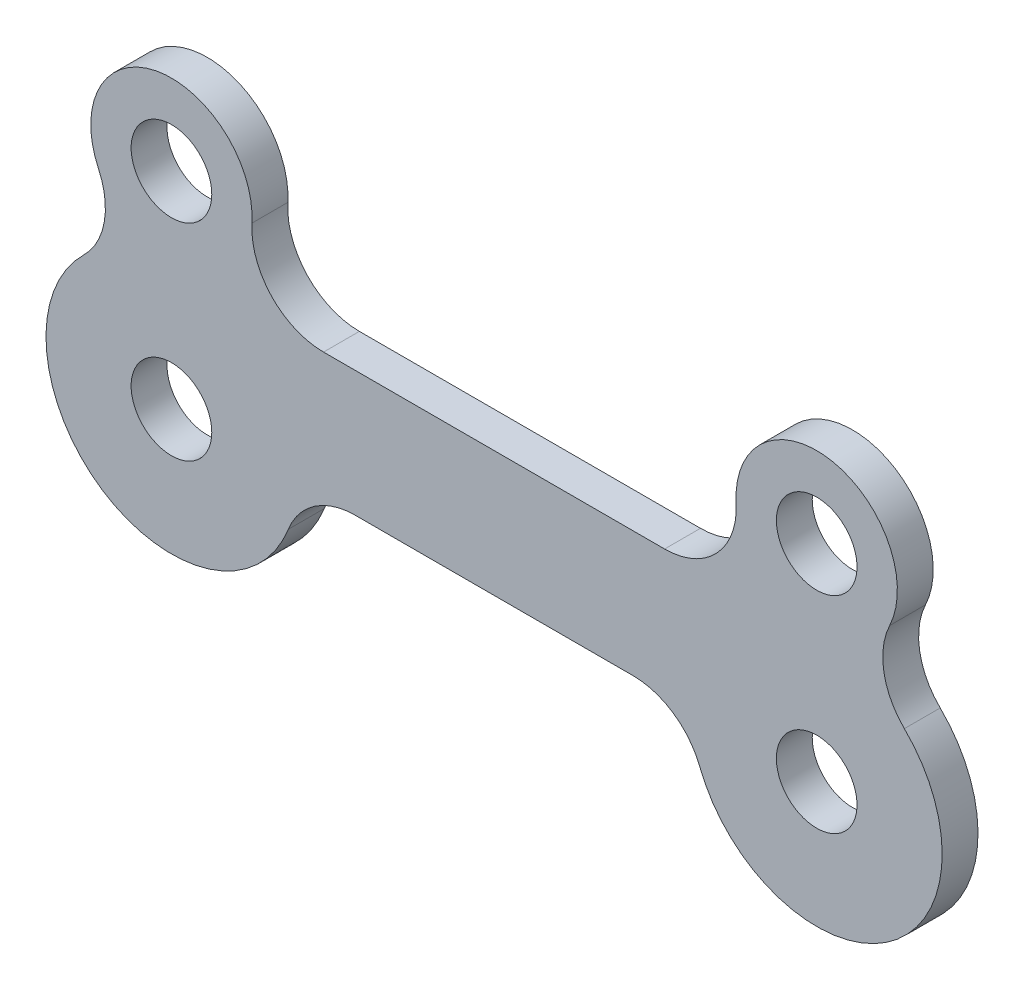
SolidWorks part; units mm, degrees
ref_plane "Front Plane" through (0, 0, 0) normal (0, 0, 1) x (1, 0, 0)
ref_plane "Top Plane" through (0, 0, 0) normal (0, 1, 0) x (1, 0, 0)
ref_plane "Right Plane" through (0, 0, 0) normal (1, 0, 0) x (0, 0, -1)
sketch "Sketch1" plane through (0, 0, 0) normal (0, 0, 1) x (1, 0, 0)
  line L0 (0, 0) -> (-14.2875, 0)
  line L1 (-14.2875, 5.5563) -> (0, 5.5563)
  line L2 (0, 5.5563) -> (0, 0)
  circle A0 centre (-14.2875, 0) radius 1.7859
  circle A1 centre (-14.2875, 0) radius 5.5563
  circle A2 centre (-14.2875, 9.1281) radius 3.5719
  circle A3 centre (-14.2875, 9.1281) radius 1.7859
  circle A4 centre (-20.388, 6.2465) radius 3.175
  circle A5 centre (-7.5523, 8.7312) radius 3.175
  circle A6 centre (-1.2023, 8.7312) radius 3.175 construction
  circle A7 centre (-7.5523, 8.7312) radius 1.7859 construction
  dimension "D2" = 3.5719
  dimension "D3" = 11.1125
  dimension "D4" = 7.1437
  dimension "D5" = 6.35
  dimension "D1" = 14.2875
extrude "Boss-Extrude1" add sketch "Sketch1" along normal blind 1.5875
fillet "Fillet1" radius 3.175 1 edges at (-8.7312, 0, 0.7937)
mirror "Mirror1" about plane through (0, 0, 1.5875) normal (1, 0, 0) of "Fillet1", "Boss-Extrude1"
